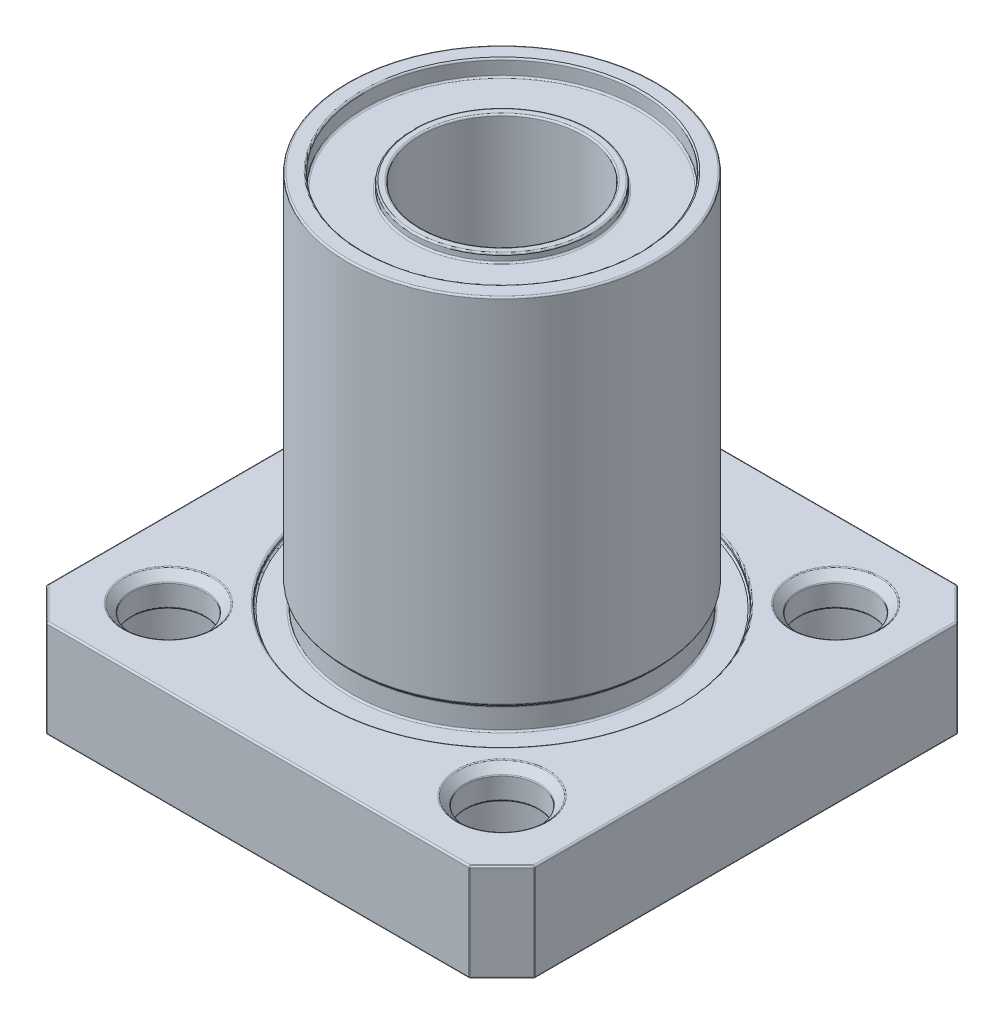
SolidWorks part; units mm, degrees
ref_plane "Front Plane" through (0, 0, 0) normal (0, 0, 1) x (1, 0, 0)
ref_plane "Top Plane" through (0, 0, 0) normal (0, 1, 0) x (1, 0, 0)
ref_plane "Right Plane" through (0, 0, 0) normal (1, 0, 0) x (0, 0, -1)
sketch "Sketch1" plane through (0, 0, 0) normal (0, 1, 0) x (1, 0, 0)
  line L1 (-15, -15) -> (15, -15)
  line L2 (-15, -15) -> (-15, 15)
  line L3 (-15, 15) -> (15, 15)
  line L4 (15, -15) -> (15, 15)
  line L5 (-15, -15) -> (15, 15) construction
  line L6 (-15, 15) -> (15, -15) construction
  point P0 (0, 0)
  dimension "D1" = 30
extrude "Boss-Extrude1" add sketch "Sketch1" along normal blind 6
sketch "Sketch2" plane through (0, 6, 0) normal (0, 1, 0) x (1, 0, 0)
  circle A0 centre (0, 0) radius 9.5
  dimension "D1" = 19
extrude "Boss-Extrude2" add sketch "Sketch2" along normal blind 23
sketch "Sketch3" plane through (0, 6, 0) normal (0, 1, 0) x (1, 0, 0)
  line L0 (-15, 15) -> (15, -15) construction
  line L1 (-15, -15) -> (15, 15) construction
  circle A0 centre (-10.253, 10.253) radius 2.25
  circle A1 centre (10.253, 10.253) radius 2.25
  circle A2 centre (10.253, -10.253) radius 2.25
  circle A3 centre (-10.253, -10.253) radius 2.25
  dimension "D1" = 4.5
extrude "Cut-Extrude3" cut sketch "Sketch3" against normal up to next
chamfer "Chamfer2" distance 2 angle 45 4 edges at (15, 3, -15) (15, 3, 15) (-15, 3, 15) (-15, 3, -15)
sketch "Sketch6" plane through (0, 29, 0) normal (0, 1, 0) x (1, 0, 0)
  circle A0 centre (0, 0) radius 8.5
  circle A1 centre (0, 0) radius 9.5 construction
  dimension "D1" = 1
extrude "Cut-Extrude4" cut sketch "Sketch6" against normal through all
sketch "Sketch7" plane through (0, 6, 0) normal (0, 1, 0) x (1, 0, 0)
  line L0 (-15, 15) -> (15, -15) construction
  circle A0 centre (0, 0) radius 10.8
  circle M5 centre (0, 0) radius 9.5
  dimension "D1" = 21.6
extrude "Cut-Extrude6" cut sketch "Sketch7" against normal blind 0.3 contours A0 M5
ref_axis "Axis2" through (0, 29, 0) along (0, -1, 0)
sketch "Sketch8" plane through (0, 0, 0) normal (0, 0, 1) x (1, 0, 0)
  line L0 (-9.5, 7.3) -> (-9.5, 5.7)
  line L1 (-9.5, 29) -> (-9.5, 5.7) construction
  line L2 (-9.5, 5.7) -> (-9.25, 5.7)
  line L3 (-9.25, 5.7) -> (-9.25, 7.05)
  line L4 (-9.25, 7.05) -> (-9.5, 7.3)
  line L5 (9.5, 6) -> (-9.5, 6) construction
  dimension "D1" = 1.6
  dimension "D2" = 0.25
  dimension "D3" = 0.25
  dimension "D4" = 0.3
revolve "Cut-Revolve1" cut sketch "Sketch8" angle 360 about axis through (0, 29, 0) along (0, -1, 0)
ref_plane "Plane1" through (0, 28, 0) normal (0, 1, 0) x (1, 0, 0)
sketch "Sketch9" plane through (0, 28, 0) normal (0, 1, 0) x (1, 0, 0)
  line L0 (-15, 15) -> (15, -15) construction
  circle A0 centre (0, 0) radius 8.5
  circle A1 centre (0, 0) radius 5
  dimension "D1" = 10
extrude "Boss-Extrude3" add sketch "Sketch9" against normal blind 27
sketch "Sketch10" plane through (0, 28, 0) normal (0, 1, 0) x (1, 0, 0)
  line L0 (-15, 15) -> (15, -15) construction
  circle A0 centre (0, 0) radius 5
  circle A1 centre (0, 0) radius 5.5
  dimension "D1" = 0.5
extrude "Boss-Extrude4" add sketch "Sketch10" along normal blind 0.5
chamfer "Chamfer3" distance 0.5 angle 45 4 edges at (10.253, 6, 12.503) (10.253, 6, -8.003) (-10.253, 6, 12.503) (-10.253, 6, -8.003)
sketch "Sketch12" plane through (0, 0, 0) normal (0, -1, 0) x (1, 0, 0)
  line L0 (-15, -15) -> (15, 15) construction
  line L1 (-15, 15) -> (15, -15) construction
  circle A0 centre (-10.253, 10.253) radius 3.75
  circle A1 centre (10.253, 10.253) radius 3.75
  circle A2 centre (-10.253, -10.253) radius 3.75
  circle A3 centre (10.253, -10.253) radius 3.75
  dimension "D1" = 7.5
extrude "Cut-Extrude7" cut sketch "Sketch12" against normal blind 4.1
fillet "Fillet2" radius 0.1 49 edges at (0, 1, 8.5) (-15, 0, 0) (14, 0, 14) (15, 3, 13) (15, 0, 0) (14, 0, -14) (15, 3, -13) (0, 0, -15) (13, 3, -15) (-15, 3, -13) (-14, 0, -14) (-13, 3, -15) (-14, 0, 14) (-15, 3, 13) (-13, 3, 15) (13, 3, 15) (0, 0, 15) (-10.253, 4.1, -12.503) (-10.253, 5.5, -12.503) (10.253, 4.1, 8.003) (10.253, 5.5, 8.003) (-10.253, 4.1, 8.003) (-10.253, 5.5, 8.003) (10.253, 4.1, -12.503) (10.253, 5.5, -12.503) (14, 6, 14) (0, 6, 15) (-14, 6, 14) (-15, 6, 0) (-14, 6, -14) (0, 6, -15) (14, 6, -14) (15, 6, 0) (0, 6, 10.8) (-10.253, 6, -13.003) (-10.253, 6, 7.503) (10.253, 6, -13.003) (10.253, 6, 7.503) (0, 5.7, 10.8) (0, 7.3, 9.5) (0, 5.7, 9.25) (0, 7.05, 9.25) (0, 29, 9.5) (0, 29, 8.5) (0, 28, 5.5) (0, 28, 8.5) (0, 28.5, 5.5) (0, 28.5, 5) (0, 0, 8.5)
chamfer "Chamfer4" distance 0.5 angle 45 4 edges at (-10.253, 0, -14.003) (10.253, 0, -14.003) (10.253, 0, 6.503) (-10.253, 0, 6.503)
